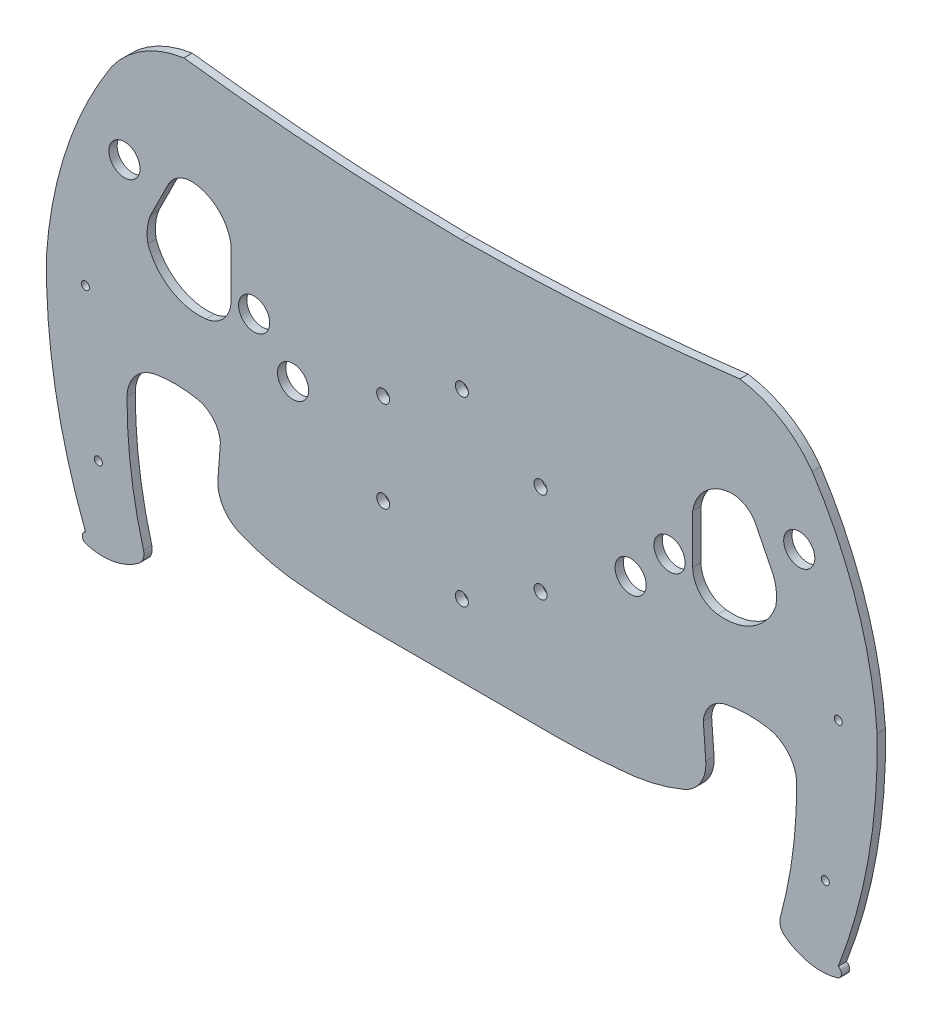
SolidWorks part; units mm, degrees
ref_plane "Front Plane" through (0, 0, 0) normal (0, 0, 1) x (1, 0, 0)
ref_plane "Top Plane" through (0, 0, 0) normal (0, 1, 0) x (1, 0, 0)
ref_plane "Right Plane" through (0, 0, 0) normal (1, 0, 0) x (0, 0, -1)
sketch "Sketch2" plane through (0, 0, 0) normal (0, 0, 1) x (1, 0, 0)
  line L1 (-37.6067, -62.7991) -> (37.6067, -62.7991)
  line L2 (93.9723, -42.1302) -> (93.028, -29.3515)
  line L3 (88.9326, 20) -> (88.9326, 38.7651)
  line L4 (113.1699, 46.6048) -> (119.9723, 33)
  line L7 (65.0277, 5) -> (65.0277, 20) construction
  line L8 (65.0277, 20) -> (80.0277, 20) construction
  line L9 (116.5711, 39.8024) -> (129.9875, 46.5106) construction
  line L10 (140.0276, -59) -> (145.0277, -3)
  line L11 (140.0276, -59) -> (153.295, -59)
  line L12 (0, 0) -> (0, 35) construction
  line L13 (-116.5711, 39.8024) -> (-129.9875, 46.5106) construction
  line L14 (-65.0277, 20) -> (-80.0277, 20) construction
  line L15 (-65.0277, 5) -> (-65.0277, 20) construction
  line L16 (-140.0276, -59) -> (-153.295, -59)
  line L17 (-140.0276, -59) -> (-145.0277, -3)
  line L18 (-113.1699, 46.6048) -> (-119.9723, 33)
  line L19 (-88.9326, 20) -> (-88.9326, 38.7651)
  line L20 (-93.9723, -42.1302) -> (-93.028, -29.3515)
  arc A0 (107.1037, 91.9201) -> (0, 84.7464) centre (-9.3181, 1026.9789) cw
  arc A15 (37.6067, -62.7991) -> (59.9723, -61.6302) centre (34.6379, 208.5652) ccw
  arc A16 (59.9723, -61.6302) -> (85.5589, -55.8163) centre (55.9536, 15.2648) ccw
  arc A17 (85.5589, -55.8163) -> (93.9723, -42.1302) centre (80.2801, -43.1421) ccw
  arc A18 (93.028, -29.3515) -> (101.8279, -19.3518) centre (104, -30.1352) cw
  arc A19 (101.8279, -19.3518) -> (118, -19.1322) centre (110.5, -62.405) cw
  arc A20 (118, -19.1322) -> (129, -32.1322) centre (115.7346, -32.2029) cw
  arc A21 (129, -32.1322) -> (122.6581, -80.0279) centre (-47.9076, -33.0754) cw
  arc A22 (122.6581, -80.0279) -> (124.4498, -85.3331) centre (127.4788, -81.355) ccw
  arc A23 (124.4498, -85.3331) -> (144.665, -89.1443) centre (138.3613, -67.062) ccw
  arc A24 (144.665, -89.1443) -> (145, -85.1322) centre (144.0743, -87.0749) ccw
  arc A25 (145, -85.1322) -> (160, 0) centre (-63.9181, -4.434) ccw
  arc A26 (160, 0) -> (135, 75) centre (2.2807, -10.9064) ccw
  arc A27 (135, 75) -> (107.1037, 91.9201) centre (101.2791, 50.8607) ccw
  circle A28 centre (145.0277, -3) radius 1.55
  circle A29 centre (80.0277, 20) radius 6
  circle A30 centre (140.0276, -59) radius 1.55
  circle A31 centre (129.9875, 46.5106) radius 6
  arc A32 (98.5965, 9.0814) -> (88.9326, 20) centre (99.9326, 20) cw
  arc A33 (88.9326, 38.7651) -> (103.1221, 52.1369) centre (104.7286, 36.2178) cw
  arc A34 (103.1221, 52.1369) -> (113.1699, 46.6048) centre (104.1362, 42.088) cw
  arc A35 (119.9723, 33) -> (120.9723, 23) centre (103.1036, 26.2631) cw
  arc A36 (120.9723, 23) -> (98.5965, 9.0814) centre (101.1473, 29.926) cw
  circle A44 centre (65.0277, 5) radius 6
  circle A46 centre (0, 35) radius 2.5
  circle A54 centre (0, 0) radius 35 construction
  circle A55 centre (30.3109, 17.5) radius 2.5
  circle A56 centre (30.3109, -17.5) radius 2.5
  circle A57 centre (0, -35) radius 2.5
  circle A58 centre (-30.3109, -17.5) radius 2.5
  circle A59 centre (-30.3109, 17.5) radius 2.5
  circle A60 centre (-65.0277, 5) radius 6
  arc A61 (-120.9723, 23) -> (-98.5965, 9.0814) centre (-101.1473, 29.926) ccw
  arc A62 (-119.9723, 33) -> (-120.9723, 23) centre (-103.1036, 26.2631) ccw
  arc A63 (-103.1221, 52.1369) -> (-113.1699, 46.6048) centre (-104.1362, 42.088) ccw
  arc A64 (-88.9326, 38.7651) -> (-103.1221, 52.1369) centre (-104.7286, 36.2178) ccw
  arc A65 (-98.5965, 9.0814) -> (-88.9326, 20) centre (-99.9326, 20) ccw
  circle A66 centre (-129.9875, 46.5106) radius 6
  circle A67 centre (-140.0276, -59) radius 1.55
  circle A68 centre (-80.0277, 20) radius 6
  circle A69 centre (-145.0277, -3) radius 1.55
  arc A70 (-135, 75) -> (-107.1037, 91.9201) centre (-101.2791, 50.8607) cw
  arc A71 (-160, 0) -> (-135, 75) centre (-2.2807, -10.9064) cw
  arc A72 (-145, -85.1322) -> (-160, 0) centre (63.9181, -4.434) cw
  arc A73 (-144.665, -89.1443) -> (-145, -85.1322) centre (-144.0743, -87.0749) cw
  arc A74 (-124.4498, -85.3331) -> (-144.665, -89.1443) centre (-138.3613, -67.062) cw
  arc A75 (-122.6581, -80.0279) -> (-124.4498, -85.3331) centre (-127.4788, -81.355) cw
  arc A76 (-129, -32.1322) -> (-122.6581, -80.0279) centre (47.9076, -33.0754) ccw
  arc A77 (-118, -19.1322) -> (-129, -32.1322) centre (-115.7346, -32.2029) ccw
  arc A78 (-101.8279, -19.3518) -> (-118, -19.1322) centre (-110.5, -62.405) ccw
  arc A79 (-93.028, -29.3515) -> (-101.8279, -19.3518) centre (-104, -30.1352) ccw
  arc A80 (-85.5589, -55.8163) -> (-93.9723, -42.1302) centre (-80.2801, -43.1421) cw
  arc A81 (-59.9723, -61.6302) -> (-85.5589, -55.8163) centre (-55.9536, 15.2648) cw
  arc A82 (-37.6067, -62.7991) -> (-59.9723, -61.6302) centre (-34.6379, 208.5652) cw
  arc A83 (-107.1037, 91.9201) -> (0, 84.7464) centre (9.3181, 1026.9789) ccw
  point P4 (0, -62.7991)
  point P119 (0, 0)
  dimension "D1" = 5
  dimension "D2" = 70
  dimension "D5" = 271.3806
  dimension "D6" = 77
  dimension "D7" = 13.7296
  dimension "D9" = 11
  dimension "D10" = 3.1
  dimension "D11" = 12
  dimension "D12" = 942.2786
  dimension "D13" = 22.3656
  dimension "D14" = 1.1689
  dimension "D15" = 8.905
  dimension "D16" = 15
  dimension "D17" = 14.1895
  dimension "D18" = 24.2373
  dimension "D19" = 13.3719
  dimension "D20" = 18.7651
  dimension "D21" = 9.6639
  dimension "D22" = 16
  dimension "D23" = 10.1
  dimension "D24" = 18.1642
  dimension "D25" = 21
  dimension "D46" = 2.152
  dimension "D49" = 223.962
  dimension "D50" = 158.096
  dimension "D53" = 41.4705
  dimension "D4" = 75.2134
  dimension "D8" = 12.8136
  dimension "D26" = 15
  dimension "D27" = 65.0277
  dimension "D28" = 5
  dimension "D29" = 22.3758
  dimension "D30" = 10
  dimension "D31" = 6.9828
  dimension "D32" = 20.6689
  dimension "D33" = 25.5866
  dimension "D34" = 8.8
  dimension "D35" = 24.972
  dimension "D36" = 9.9997
  dimension "D37" = 10.2193
  dimension "D38" = 13
  dimension "D39" = 11
  dimension "D40" = 47.8957
  dimension "D41" = 53.2009
  dimension "D42" = 6.3419
  dimension "D43" = 1.7918
  dimension "D44" = 20.2152
  dimension "D45" = 3.8112
  dimension "D47" = 4.012
  dimension "D48" = 15
  dimension "D51" = 25
  dimension "D52" = 75
  dimension "D54" = 27.7991
  dimension "D55" = 27.8963
  dimension "D56" = 16.9201
  dimension "D57" = 49.7464
  dimension "D58" = 26.1322
  dimension "D59" = 4.9724
  dimension "D60" = 84.898
  dimension "D61" = 56.2228
  dimension "D3" = 6
extrude "Boss-Extrude1" add sketch "Sketch2" along normal blind 3.2
